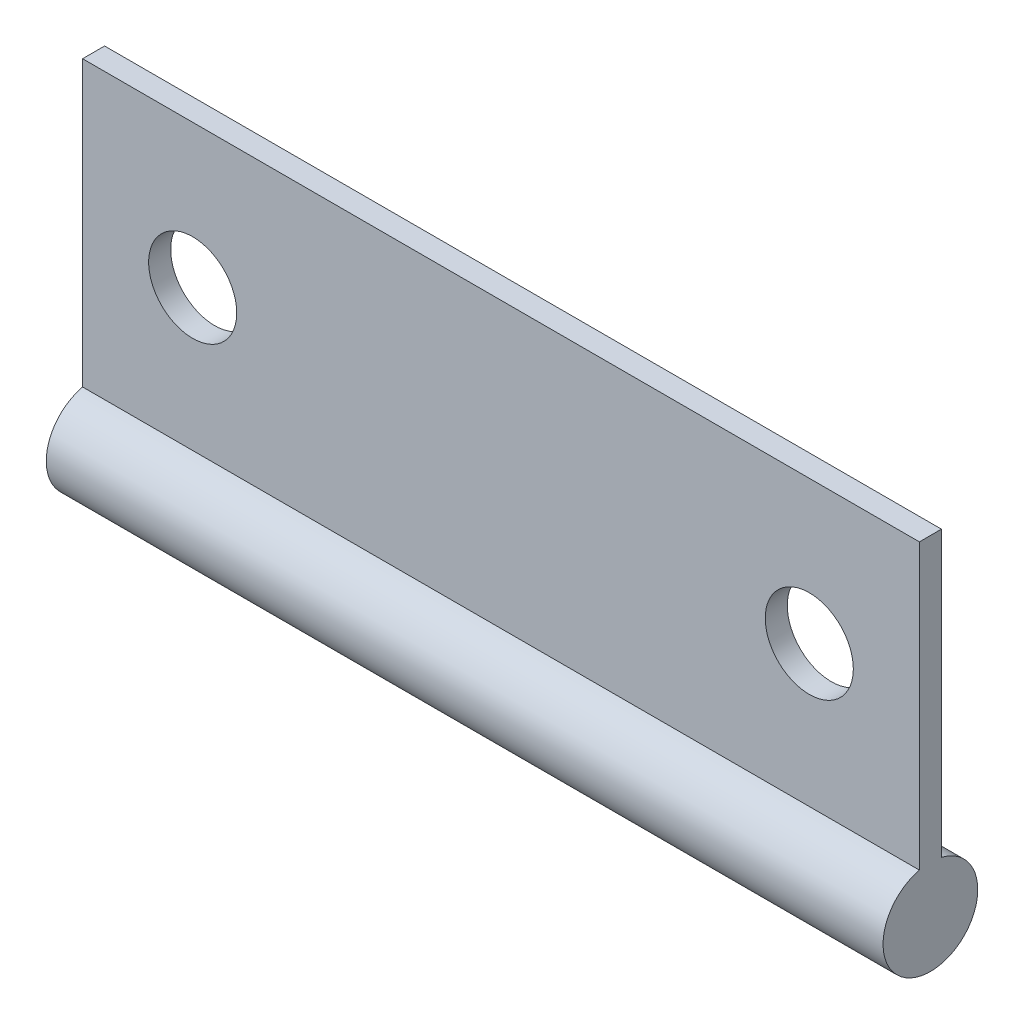
SolidWorks part; units mm, degrees
ref_plane "前视基准面" through (0, 0, 0) normal (0, 0, 1) x (1, 0, 0)
ref_plane "上视基准面" through (0, 0, 0) normal (0, 1, 0) x (1, 0, 0)
ref_plane "右视基准面" through (0, 0, 0) normal (1, 0, 0) x (0, 0, -1)
sketch "草图1" plane through (0, 0, 0) normal (0, 0, 1) x (1, 0, 0)
  line L13 (-40.8185, 12.5196) -> (-12.8185, 12.5196) construction
  line L14 (-40.8185, 12.5196) -> (-40.8185, -4.4804) construction
  line L15 (-40.8185, -4.4804) -> (-12.8185, -4.4804) construction
  line L16 (-12.8185, 12.5196) -> (-12.8185, -4.4804) construction
  line L17 (-45.8185, 19.0196) -> (-7.8185, 19.0196)
  line L18 (-45.8185, 19.0196) -> (-45.8185, -10.9804)
  line L19 (-45.8185, -10.9804) -> (-7.8185, -10.9804)
  line L20 (-7.8185, 19.0196) -> (-7.8185, -10.9804)
  circle A0 centre (-40.8185, 12.5196) radius 2
  circle A1 centre (-12.8185, 12.5196) radius 2
  circle A2 centre (-40.8185, -4.4804) radius 2
  circle A3 centre (-12.8185, -4.4804) radius 2
  dimension "D3" = 30
  dimension "D1" = 17
  dimension "D2" = 28
  dimension "D4" = 38
  dimension "D5" = 5
  dimension "D6" = 6.5
extrude "凸台-拉伸1" add sketch "草图1" along normal blind 1
sketch "草图2" plane through (0, 0, 1) normal (0, 0, 1) x (1, 0, 0)
  line L0 (-7.8185, -10.9804) -> (-7.8185, 19.0196) construction
  line L1 (-45.8185, -10.9804) -> (-7.8185, -10.9804)
  line L2 (-45.8185, -10.9804) -> (-45.8185, 4.0196)
  line L3 (-45.8185, 4.0196) -> (-7.8185, 4.0196)
  line L4 (-7.8185, -10.9804) -> (-7.8185, 4.0196)
extrude "切除-拉伸1" cut sketch "草图2" against normal blind 1
sketch "草图4" plane through (-45.8185, 0, 0) normal (-1, 0, 0) x (0, 0, 1)
  line L0 (0, 4.0196) -> (1, 4.0196) construction
  circle A0 centre (0.5, 4.0196) radius 2.15
extrude "凸台-拉伸2" add sketch "草图4" against normal blind 38
